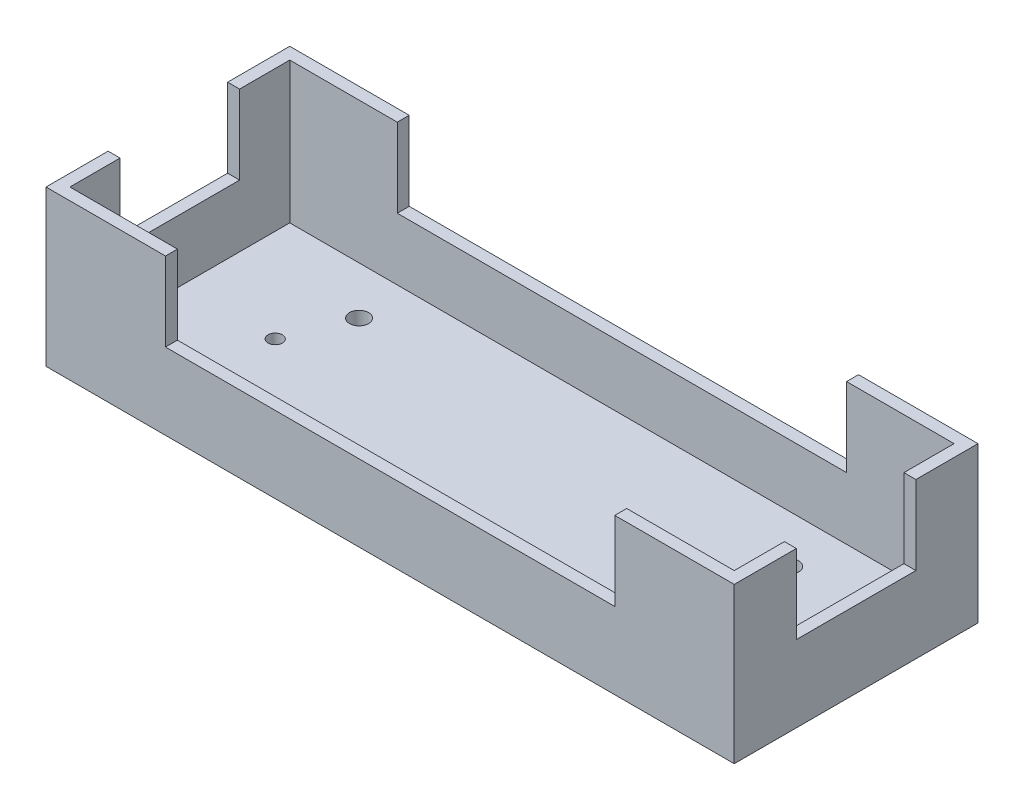
SolidWorks part; units mm, degrees
ref_plane "Front Plane" through (0, 0, 0) normal (0, 0, 1) x (1, 0, 0)
ref_plane "Top Plane" through (0, 0, 0) normal (0, 1, 0) x (1, 0, 0)
ref_plane "Right Plane" through (0, 0, 0) normal (1, 0, 0) x (0, 0, -1)
sketch "Sketch1" plane through (0, 0, 0) normal (0, 1, 0) x (1, 0, 0)
  line L1 (72, 25.5) -> (-72, 25.5)
  line L2 (72, 25.5) -> (72, -25.5)
  line L3 (72, -25.5) -> (-72, -25.5)
  line L4 (-72, 25.5) -> (-72, -25.5)
  line L5 (72, 25.5) -> (-72, -25.5) construction
  line L6 (72, -25.5) -> (-72, 25.5) construction
  point P0 (0, 0)
  dimension "D1" = 144
  dimension "D2" = 51
extrude "Boss-Extrude1" add sketch "Sketch1" along normal blind 3
sketch "Sketch2" plane through (0, 3, 0) normal (0, 1, 0) x (1, 0, 0)
  line L1 (72, 25.5) -> (-72, 25.5)
  line L2 (72, 25.5) -> (72, -25.5)
  line L3 (72, -25.5) -> (-72, -25.5)
  line L4 (-72, 25.5) -> (-72, -25.5)
  line L5 (72, 25.5) -> (-72, -25.5) construction
  line L6 (72, -25.5) -> (-72, 25.5) construction
  line L7 (69.5, -23) -> (-69.5, -23)
  line L8 (69.5, -23) -> (69.5, 23)
  line L9 (69.5, 23) -> (-69.5, 23)
  line L10 (-69.5, -23) -> (-69.5, 23)
  line L11 (69.5, -23) -> (-69.5, 23) construction
  line L12 (69.5, 23) -> (-69.5, -23) construction
  point P0 (0, 0)
  point P7 (0, 0)
  dimension "D1" = 2.5
  dimension "D2" = 2.5
extrude "Boss-Extrude2" add sketch "Sketch2" along normal blind 16 from surface at -3 starting at face at (0, 0, 0)
sketch "Sketch3" plane through (0, 16, 0) normal (0, 1, 0) x (1, 0, 0)
  line L0 (0, 25.5) -> (0, -25.5) construction
  line L1 (-72, 25.5) -> (72, 25.5) construction
  line L2 (72, -25.5) -> (-72, -25.5) construction
  line L3 (-72, 0) -> (72, 0) construction
  line L4 (-72, -25.5) -> (-72, 25.5) construction
  line L5 (72, 25.5) -> (72, -25.5) construction
  line L6 (-72, 25.5) -> (-72, 12.5)
  line L7 (-72, 12.5) -> (-69.5, 12.5)
  line L8 (-69.5, -23) -> (-69.5, 23) construction
  line L9 (-69.5, 12.5) -> (-69.5, 23)
  line L10 (-69.5, 23) -> (-47, 23)
  line L11 (-69.5, 23) -> (69.5, 23) construction
  line L12 (-47, 23) -> (-47, 25.5)
  line L13 (-47, 25.5) -> (-72, 25.5)
  line L14 (47, 25.5) -> (72, 25.5)
  line L15 (47, 23) -> (47, 25.5)
  line L16 (69.5, 23) -> (47, 23)
  line L17 (69.5, 12.5) -> (69.5, 23)
  line L18 (72, 12.5) -> (69.5, 12.5)
  line L19 (72, 25.5) -> (72, 12.5)
  line L20 (72, -25.5) -> (72, -12.5)
  line L21 (72, -12.5) -> (69.5, -12.5)
  line L22 (69.5, -12.5) -> (69.5, -23)
  line L23 (69.5, -23) -> (47, -23)
  line L24 (47, -23) -> (47, -25.5)
  line L25 (47, -25.5) -> (72, -25.5)
  line L26 (-47, -25.5) -> (-72, -25.5)
  line L27 (-47, -23) -> (-47, -25.5)
  line L28 (-69.5, -23) -> (-47, -23)
  line L29 (-69.5, -12.5) -> (-69.5, -23)
  line L30 (-72, -12.5) -> (-69.5, -12.5)
  line L31 (-72, -25.5) -> (-72, -12.5)
  dimension "D1" = 13
  dimension "D2" = 25
extrude "Boss-Extrude3" add sketch "Sketch3" along normal blind 16.5
sketch "Sketch4" plane through (0, 0, 0) normal (0, -1, 0) x (1, 0, 0)
  line L0 (-72, 0) -> (72, 0) construction
  line L1 (-72, -25.5) -> (-72, 25.5) construction
  line L2 (72, 25.5) -> (72, -25.5) construction
  line L3 (-45, 25.5) -> (-45, -25.5) construction
  line L4 (-72, 25.5) -> (72, 25.5) construction
  line L5 (72, -25.5) -> (-72, -25.5) construction
  line L6 (-47, -25.5) -> (-72, -25.5) construction
  line L7 (0, 25.5) -> (0, -25.5) construction
  line L8 (45, 25.5) -> (45, -25.5) construction
  circle A0 centre (-45, -13) radius 2
  circle A1 centre (-45, 13) radius 2
  circle A2 centre (45, 13) radius 2
  circle A3 centre (45, -13) radius 2
  circle A4 centre (-50, -0.45) radius 1.5
  circle A5 centre (50, -0.45) radius 1.5
  point P16 (-59.5, -25.5)
  point P19 (-47, 13)
  point P28 (47, 13)
  dimension "D3" = 4
  dimension "D7" = 3
  dimension "D1" = 12.5
  dimension "D2" = 12.5
  dimension "D4" = 25
  dimension "D5" = 22
  dimension "D6" = 25.05
extrude "Cut-Extrude1" cut sketch "Sketch4" against normal through all
equation "\"D2@Sketch4\"=\"D1@Sketch4\""
